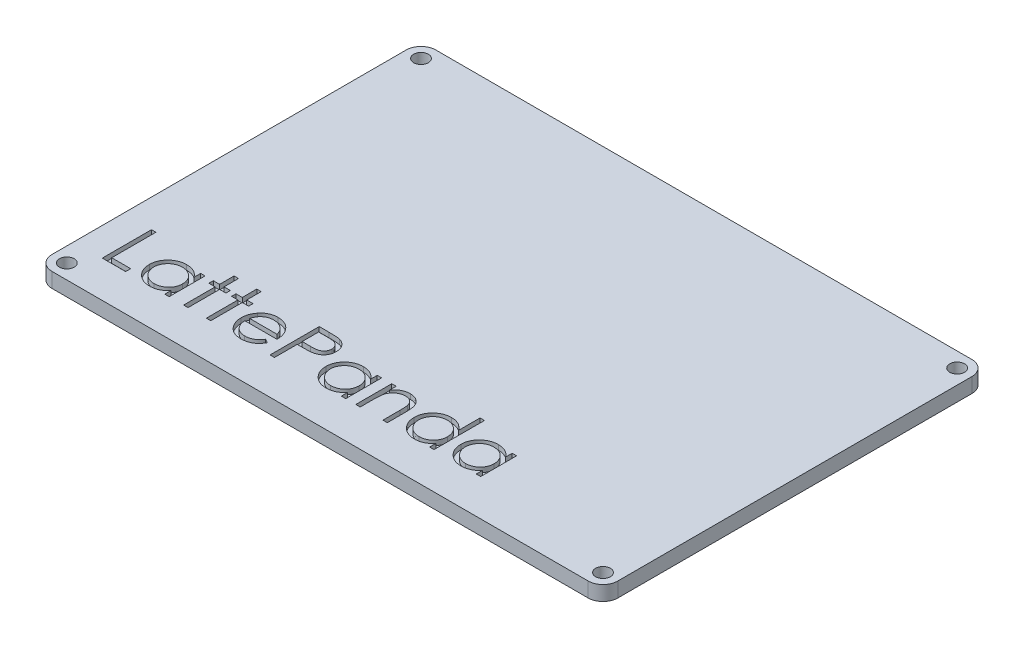
SolidWorks part; units mm, degrees
ref_plane "Front Plane" through (0, 0, 0) normal (0, 0, 1) x (1, 0, 0)
ref_plane "Top Plane" through (0, 0, 0) normal (0, 1, 0) x (1, 0, 0)
ref_plane "Right Plane" through (0, 0, 0) normal (1, 0, 0) x (0, 0, -1)
sketch "Sketch1" plane through (0, 0, 0) normal (0, 1, 0) x (1, 0, 0)
  line L1 (-54.5, 39) -> (54.5, 39)
  line L2 (-57.5, 36) -> (-57.5, -36)
  line L3 (-54.5, -39) -> (54.5, -39)
  line L4 (57.5, 36) -> (57.5, -36)
  line L5 (-57.5, 39) -> (57.5, -39) construction
  line L6 (-57.5, -39) -> (57.5, 39) construction
  arc A0 (-57.5, 36) -> (-54.5, 39) centre (-54.5, 36) cw
  arc A1 (57.5, 36) -> (54.5, 39) centre (54.5, 36) ccw
  arc A2 (54.5, -39) -> (57.5, -36) centre (54.5, -36) ccw
  arc A3 (-54.5, -39) -> (-57.5, -36) centre (-54.5, -36) cw
  circle A4 centre (-54.5, 36) radius 1.5
  circle A5 centre (54.5, 36) radius 1.5
  circle A6 centre (54.5, -36) radius 1.5
  circle A7 centre (-54.5, -36) radius 1.5
  point P0 (0, 0)
  dimension "D3" = 3
  dimension "D4" = 3
  dimension "D1" = 115
  dimension "D2" = 78
extrude "Boss-Extrude1" add sketch "Sketch1" along normal blind 3
sketch "Sketch2" plane through (0, 3, 0) normal (0, 1, 0) x (1, 0, 0)
  text T0 "LattePanda" font "Century Gothic" height 10
extrude "Cut-Extrude1" cut sketch "Sketch2" against normal blind 1
